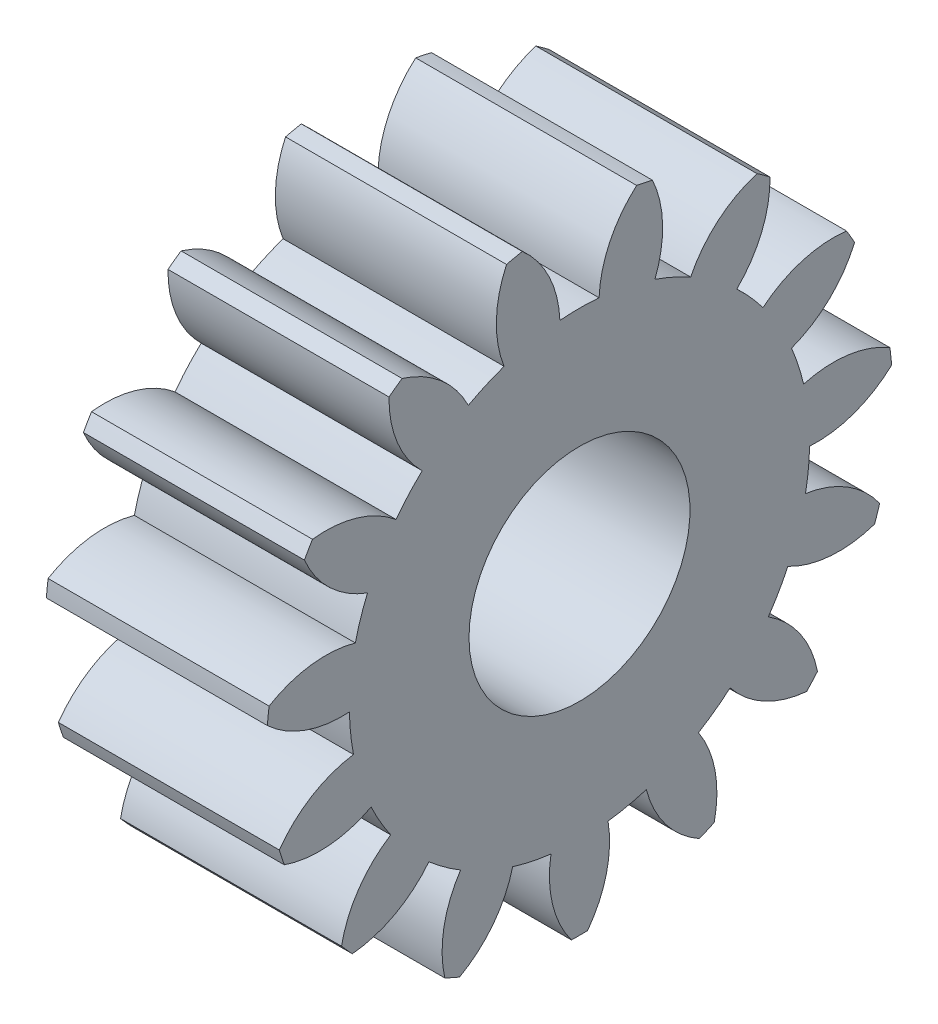
SolidWorks part; units mm, degrees
ref_plane "Plane1" through (0, 0, 0) normal (0, 0, 1) x (1, 0, 0)
ref_plane "Plane2" through (0, 0, 0) normal (0, 1, 0) x (1, 0, 0)
ref_plane "Plane3" through (0, 0, 0) normal (1, 0, 0) x (0, 0, -1)
other "Configuration Table"
sketch "HoldingSke" plane through (0, 0, 0) normal (0, 1, 0) x (1, 0, 0)
  line L0 (0, 0) -> (1.9319, -0.5176)
  line L1 (-15, 0) -> (100, 0) construction
  line L2 (0, 0) -> (-2.1039, 2.3779)
  line L3 (0, 0) -> (-11.863, 4.5341)
  line L4 (0, 0) -> (8.3417, 2.2352)
  line L5 (0, 0) -> (-46.8476, -17.4728)
  line L6 (0, 0) -> (-2.4869, -1.6779)
  line L7 (-2.1039, 2.3779) -> (8.6586, 51.2059)
  line L8 (-76.2, 54.61) -> (-75.7, 54.61)
  line L9 (-71.009, 38.7566) -> (-53.1078, 45.2721)
  line L10 (-76.2, 71.12) -> (104.1128, 71.12)
  line L11 (0, 0) -> (-3, 0)
  line L12 (-76.2, 101.6) -> (-76.181, 101.6)
  line L13 (24.9733, 27.94) -> (52.9518, 28.4284)
  line L14 (24.9733, 27.94) -> (24.9743, 27.94)
  line L15 (24.9733, 27.94) -> (100.4006, 29.5858)
  line L16 (-63.627, -0.5) -> (-12.827, -0.5)
  circle A0 centre (0, 0) radius 1.5
  circle A1 centre (0, 0) radius 3.124
  circle A2 centre (0, 0) radius 37.5
  circle A3 centre (0, 0) radius 1.5
  dimension "MHD" = 6.248
  dimension "Hub_dia" = 75
  dimension "Bore" = 3
  dimension "MBD" = 3
  dimension "Num_teeth" = 15
  dimension "Pitch" = 2
  dimension "Overall_len" = 50
  dimension "Show_teeth" = 15
  dimension "Thickness" = 3
  dimension "OAL" = 50.0001
  dimension "T_dim" = 0.5
  dimension "Ap" = 20
  dimension "H" = 19.05
  dimension "Pitch_radius" = 180.3128
  dimension "Width" = 3
  dimension "Backlash" = 0.019
  dimension "Addendum_fac" = 1
  dimension "Dedendum_fac" = 1.25
  dimension "Clearance_fac" = 0.25
  dimension "Dedendum_add" = 0.001
  dimension "Module" = 0.5
sketch "BasProSke" plane through (0, 0, 0) normal (0, 1, 0) x (1, 0, 0)
  line L0 (-10, 0) -> (60, 0) construction
  line L1 (0, 0) -> (0, 4.25)
  line L2 (0, 0) -> (3, 0)
  line L3 (3, 0) -> (3, 4.25)
  line L4 (3, 4.25) -> (0, 4.25)
  dimension "Thickness" = 3
  dimension "Diameter" = 8.5
revolve "Base-Revolve" add sketch "BasProSke" angle 360 about L0
sketch "TooCutSke" plane through (0, 0, 0) normal (1, 0, 0) x (0, 0, -1)
  line L1 (0, 0) -> (0, 107) construction
  line L2 (0, 0) -> (-0.4252, 3.7258) construction
  line L3 (0, 0) -> (-1.5522, 7.3025) construction
  line L4 (-0.4252, 3.7258) -> (-0.7761, 3.6512) construction
  arc A0 (0.2658, 3.1127) -> (-0.2658, 3.1127) centre (0, 0) ccw
  arc A1 (0.8008, 4.1997) -> (-0.8008, 4.1997) centre (0, 0) ccw
  circle A2 centre (0, 0) radius 3.75 construction
  circle A3 centre (0, 0) radius 3.5238 construction
  arc A4 (-0.2658, 3.1127) -> (-0.8008, 4.1997) centre (-1.7645, 3.0503) ccw
  arc A5 (0.8008, 4.1997) -> (0.2658, 3.1127) centre (1.7645, 3.0503) ccw
  dimension "Root_dia" = 6.248
  dimension "Overcut_dia" = 8.5508
  dimension "Pitch_dia" = 7.5
  dimension "Base_dia" = 7.0477
  dimension "Flank_rad" = 1.5
  dimension "Half_ang" = 12
  dimension "Half_CT" = 0.3587
extrude "ToothCut" cut sketch "TooCutSke" along normal through all
fillet "Breaks" [suppressed] radius 0.01
fillet "RootFillets" [suppressed] radius 0.126
pattern_circular "TeethCuts" count 15 every 24 about axis through (-10, 0, 0) along (1, 0, 0) of "ToothCut", "RootFillets", "Breaks"
sketch "HubNeaOneSke" plane through (0, 0, 0) normal (-1, 0, 0) x (0, 0, 1)
  circle A0 centre (0, 0) radius 3.124
  dimension "Diameter" = 6.248
extrude "HubNearOne" [suppressed] add sketch "HubNeaOneSke" along normal blind 47.0001
sketch "HubNeaBotSke" plane through (0, 0, 0) normal (-1, 0, 0) x (0, 0, 1)
  circle A0 centre (0, 0) radius 3.124
  dimension "Diameter" = 6.248
extrude "HubNearBoth" [suppressed] add sketch "HubNeaBotSke" along normal blind 23.5
ref_plane "FarPln" through (3, 0, 0) normal (1, 0, 0) x (0, 0, -1)
sketch "HubFarSke" plane through (3, 0, 0) normal (1, 0, 0) x (0, 0, -1)
  circle A0 centre (0, 0) radius 3.124
  dimension "Diameter" = 6.248
extrude "HubFar" [suppressed] add sketch "HubFarSke" along normal blind 23.5
sketch "BorSke" plane through (0, 0, 0) normal (1, 0, 0) x (0, 0, -1)
  circle A0 centre (0, 0) radius 1.5
  dimension "Diameter" = 3
extrude "Bore" cut sketch "BorSke" along normal mid plane 100.0001
sketch "KeySke" plane through (0, 0, 0) normal (1, 0, 0) x (0, 0, -1)
  line L0 (-0.6, 0) -> (-0.6, 2)
  line L1 (-0.6, 2) -> (0.6, 2)
  line L2 (0.6, 2) -> (0.6, 0)
  line L3 (0, 0) -> (0, 34) construction
  line L4 (-0.6, 0) -> (0.6, 0)
  dimension "Offset" = 2
  dimension "Width" = 1.2
extrude "Keyway" [suppressed] cut sketch "KeySke" along normal mid plane 100.0001
pattern_circular "Keyway2" [suppressed] count 2 every 90 about axis through (-10, 0, 0) along (1, 0, 0)
equation "' \"Module@HoldingSke\" = 6.35"
equation "' \"Num_teeth@HoldingSke\" = 12"
equation "' \"Ap@HoldingSke\" =  20"
equation "' \"Ap@HoldingSke\" = 20"
equation "' \"Width@HoldingSke\" = 0.5 * 25.4"
equation "' \"Hub_dia@HoldingSke\"= 1 * 25.4"
equation "' \"Hub_dia@HoldingSke\" = 1 * 25.4"
equation "' \"Overall_len@HoldingSke\" = 1.0 * 25.4"
equation "' \"Bore@HoldingSke\" = 0.75 * 25.4"
equation "' \"T_dim@HoldingSke\" = 0.1 * 25.4"
equation "' \"Width@KeySke\" = 0.25 * 25.4"
equation "' \"Show_teeth@HoldingSke\" = 13"
equation "' \"Backlash@HoldingSke\" = 0.009 * 25.4"
equation "' \"Addendum_fac@HoldingSke\" = 1.0"
equation "' \"Dedendum_fac@HoldingSke\" = 1.25"
equation "' \"Dedendum_add@HoldingSke\" = 0.00005 * 25.4"
equation "' \"Clearance_fac@HoldingSke\" = 0.25"
equation "\"Pitch@HoldingSke\" = 1 / \"Module@HoldingSke\""
equation "\"Overcut_dia@TooCutSke\" = (\"Num_teeth@HoldingSke\" + 2 * \"Addendum_fac@HoldingSke\") / \"Pitch@HoldingSke\" + 0.002 * 25.4"
equation "\"Pitch_dia@TooCutSke\" = \"Num_teeth@HoldingSke\" / \"Pitch@HoldingSke\""
equation "\"Base_dia@TooCutSke\" = \"Num_teeth@HoldingSke\" / \"Pitch@HoldingSke\" * cos((\"Ap@HoldingSke\"  * 3.14159265 / 180))"
equation "\"Root_dia@TooCutSke\" = (\"Num_teeth@HoldingSke\" + 2) / \"Pitch@HoldingSke\" - 2 * (\"Addendum_fac@HoldingSke\" + \"Dedendum_fac@HoldingSke\") / \"Pitch@HoldingSke\" - \"Dedendum_add@HoldingSke\" * 2"
equation "\"Half_ang@TooCutSke\" = 180 / \"Num_teeth@HoldingSke\""
equation "\"Half_CT@TooCutSke\" = \"Num_teeth@HoldingSke\" / \"Pitch@HoldingSke\" * sin((3.14159265 / 2 / \"Num_teeth@HoldingSke\")) / 2 - 7 * \"Backlash@HoldingSke\" / 4"
equation "\"Flank_rad@TooCutSke\" = \"Num_teeth@HoldingSke\" / \"Pitch@HoldingSke\" / 5"
equation "\"Radius@RootFillets\" = \"Clearance_fac@HoldingSke\" / \"Pitch@HoldingSke\" + \"Dedendum_add@HoldingSke\""
equation "\"Break_rad@Breaks\" = 0.02 / \"Pitch@HoldingSke\""
equation "\"Thickness@HoldingSke\" = \"Width@HoldingSke\""
equation "\"OAL@HoldingSke\" = \"Thickness@HoldingSke\""
equation "\"MHD@HoldingSke\" = (\"Num_teeth@HoldingSke\" + 2) / \"Pitch@HoldingSke\" - 2 * (\"Addendum_fac@HoldingSke\" + \"Dedendum_fac@HoldingSke\")  / \"Pitch@HoldingSke\" - \"Dedendum_add@HoldingSke\" * 2"
equation "\"MBD@HoldingSke\" = (\"Num_teeth@HoldingSke\" + 2) / \"Pitch@HoldingSke\" - 2 * (\"Addendum_fac@HoldingSke\" + \"Dedendum_fac@HoldingSke\")  / \"Pitch@HoldingSke\" - \"Dedendum_add@HoldingSke\" * 2 - 0.002 * 25.4"
equation "\"MHD@HoldingSke\" = ((sgn( \"MHD@HoldingSke\" - \"Hub_dia@HoldingSke\" )-1)*( \"MHD@HoldingSke\" - \"Hub_dia@HoldingSke\" ))/-2+ \"Hub_dia@HoldingSke\""
equation "\"MBD@HoldingSke\" = ((sgn( \"MBD@HoldingSke\" - \"Bore@HoldingSke\" )-1)*( \"MBD@HoldingSke\" - \"Bore@HoldingSke\" ))/-2+ \"Bore@HoldingSke\""
equation "\"OAL@HoldingSke\" = ((sgn( \"OAL@HoldingSke\" - \"Overall_len@HoldingSke\" )+1)*( \"OAL@HoldingSke\" - \"Overall_len@HoldingSke\" ))/2 + \"Overall_len@HoldingSke\" + 0.000002 * 25.4"
equation "\"Num_teeth@TeethCuts\" = int( \"Show_teeth@HoldingSke\" ) + 1"
equation "\"Num_teeth@TeethCuts\" = ((sgn( \"Num_teeth@TeethCuts\" - \"Num_teeth@HoldingSke\" )-1)*( \"Num_teeth@TeethCuts\" - \"Num_teeth@HoldingSke\" ))/-2+ \"Num_teeth@HoldingSke\""
equation "\"Num_teeth@TeethCuts\" = ((sgn( \"Num_teeth@TeethCuts\" - 2.0)+1)*( \"Num_teeth@TeethCuts\" - 2.0))/2 +2.0"
equation "\"Angle@TeethCuts\" = 360.0 / \"Num_teeth@HoldingSke\""
equation "\"Diameter@BasProSke\" = (\"Num_teeth@HoldingSke\" + 2 * \"Addendum_fac@HoldingSke\") / \"Pitch@HoldingSke\""
equation "\"Thickness@BasProSke\"  = \"Thickness@HoldingSke\""
equation "' \"Fillet_rad@BasProSke\" =  \"Thickness@HoldingSke\" * 0.05"
equation "' \"Fillet_rad@BasProSke\" = \"Thickness@HoldingSke\" * 0.05"
equation "\"MHD@HoldingSke\" = ((sgn( \"MHD@HoldingSke\" - \"Root_dia@TooCutSke\" )-1)*( \"MHD@HoldingSke\" - \"Root_dia@TooCutSke\" ))/-2+ \"Root_dia@TooCutSke\""
equation "\"Diameter@HubNeaOneSke\" = \"MHD@HoldingSke\""
equation "\"Length@HubNearOne\" = \"OAL@HoldingSke\" - \"Thickness@BasProSke\""
equation "\"Diameter@HubNeaBotSke\" = \"MHD@HoldingSke\""
equation "\"Length@HubNearBoth\" = ( \"OAL@HoldingSke\" - \"Thickness@BasProSke\" ) / 2.0"
equation "\"Thickness@FarPln\" = \"Thickness@BasProSke\""
equation "\"Diameter@HubFarSke\" = \"MHD@HoldingSke\""
equation "\"Length@HubFar\" = ( \"OAL@HoldingSke\" - \"Thickness@BasProSke\" ) / 2.0"
equation "\"Diameter@BorSke\" = \"MBD@HoldingSke\""
equation "\"D1@Bore\" = \"OAL@HoldingSke\" * 2.0"
equation "\"D1@Keyway\" = \"OAL@HoldingSke\" * 2.0"
equation "\"Offset@KeySke\" = \"T_dim@HoldingSke\" + \"MBD@HoldingSke\" / 2.0"
